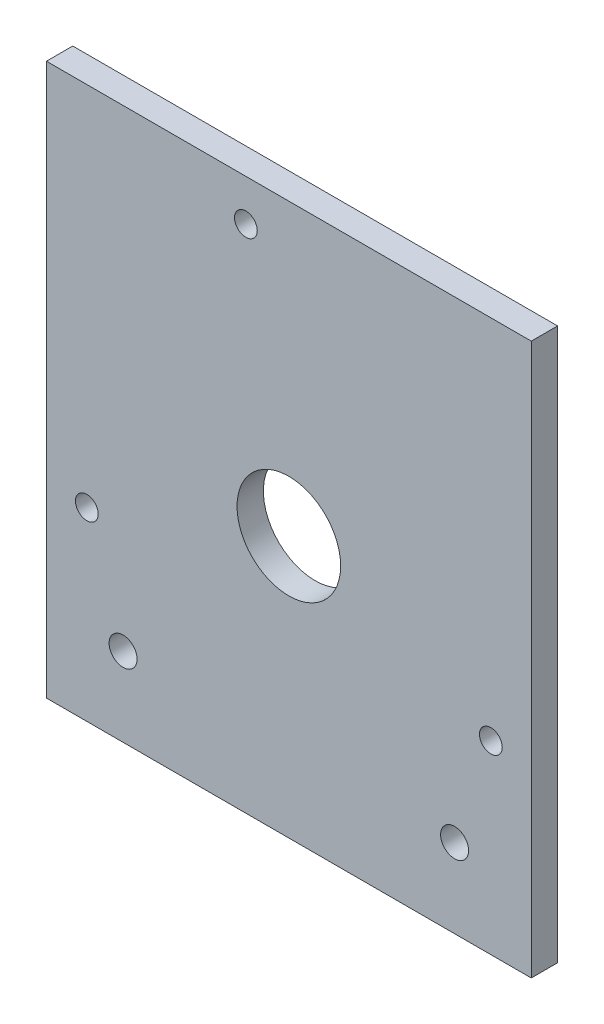
SolidWorks part; units mm, degrees
material "Alumina"
ref_plane "Front Plane" through (0, 0, 0) normal (0, 0, 1) x (1, 0, 0)
ref_plane "Top Plane" through (0, 0, 0) normal (0, 1, 0) x (1, 0, 0)
ref_plane "Right Plane" through (0, 0, 0) normal (1, 0, 0) x (0, 0, -1)
sketch "Sketch1" plane through (0, 0, 0) normal (0, 0, 1) x (1, 0, 0)
  line L0 (48.75, -18.4) -> (-48.75, -18.4) construction
  line L1 (-48.75, -18.4) -> (-10.369, 60.0104) construction
  line L2 (-10.369, 60.0104) -> (48.75, -18.4) construction
  line L7 (0, 70) -> (0, -63.1) construction
  line L13 (-58.5, 70) -> (58.5, 70)
  line L14 (-58.5, 70) -> (-58.5, -63.1)
  line L15 (-58.5, -63.1) -> (58.5, -63.1)
  line L16 (58.5, 70) -> (58.5, -63.1)
  line L17 (-58.5, -25) -> (58.5, -25) construction
  line L18 (-58.5, -44.05) -> (58.5, -44.05) construction
  circle A0 centre (-48.75, -18.4) radius 2.75
  circle A1 centre (48.75, -18.4) radius 2.75
  circle A2 centre (-10.369, 60.0104) radius 2.75
  circle A6 centre (-40, -44.05) radius 3.38
  circle A7 centre (40, -44.05) radius 3.38
  circle A8 centre (0, 0) radius 12.5
  point P0 (-10.369, 60.0104)
  point P1 (-48.75, -18.4)
  point P2 (48.75, -18.4)
  point P5 (0, -18.4)
  point P18 (-40, -44.05)
  point P21 (40, -44.05)
  dimension "D4" = 5.5
  dimension "D13" = 6.76
  dimension "D14" = 25
  dimension "D1" = 97.5
  dimension "D2" = 87.3
  dimension "D3" = 98.2
  dimension "D5" = 117
  dimension "D6" = 133.1
  dimension "D7" = 38.1
  dimension "D8" = 25
  dimension "D9" = 6.6
  dimension "D10" = 19.05
  dimension "D11" = 40
  dimension "D12" = 40
extrude "Boss-Extrude1" add sketch "Sketch1" along normal blind 6.35
equation "\"universalHoleSize\"= 6.76mm"
equation "\"D13@Sketch1\"=\"universalHoleSize\""
